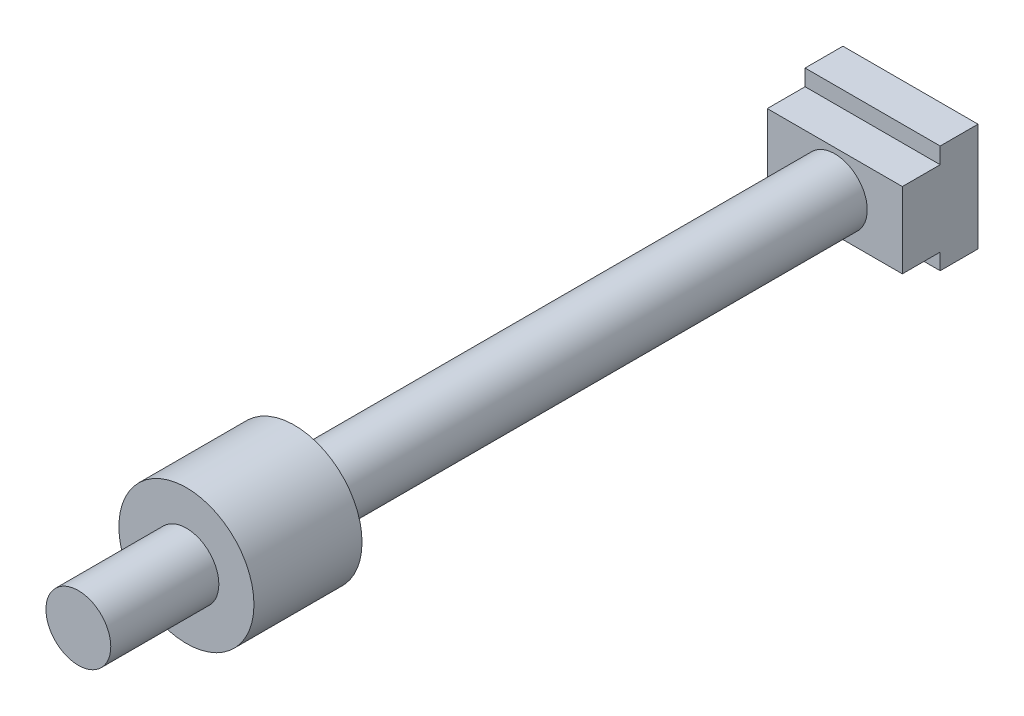
SolidWorks part; units mm, degrees
ref_plane "Front Plane" through (0, 0, 0) normal (0, 0, 1) x (1, 0, 0)
ref_plane "Top Plane" through (0, 0, 0) normal (0, 1, 0) x (1, 0, 0)
ref_plane "Right Plane" through (0, 0, 0) normal (1, 0, 0) x (0, 0, -1)
sketch "Sketch1" plane through (0, 0, 0) normal (0, 0, 1) x (1, 0, 0)
  circle A0 centre (0, 0) radius 6
  dimension "D1" = 12
extrude "Boss-Extrude1" add sketch "Sketch1" along normal blind 100
sketch "Sketch2" plane through (0, 0, 100) normal (0, 0, 1) x (1, 0, 0)
  circle A0 centre (0, 0) radius 12.5
  dimension "D1" = 25
extrude "Boss-Extrude2" add sketch "Sketch2" along normal blind 20
sketch "Sketch3" plane through (0, 0, 120) normal (0, 0, 1) x (1, 0, 0)
  circle A0 centre (0, 0) radius 6
  dimension "D1" = 12
extrude "Boss-Extrude3" add sketch "Sketch3" along normal blind 20
sketch "Sketch4" plane through (0, 0, 0) normal (0, 0, -1) x (-1, 0, 0)
  line L1 (-12.5, -7) -> (12.5, -7)
  line L2 (-12.5, -7) -> (-12.5, 7)
  line L3 (-12.5, 7) -> (12.5, 7)
  line L4 (12.5, -7) -> (12.5, 7)
  line L5 (-12.5, -7) -> (12.5, 7) construction
  line L6 (-12.5, 7) -> (12.5, -7) construction
  point P0 (0, 0)
  dimension "D1" = 14
  dimension "D2" = 25
extrude "Boss-Extrude4" add sketch "Sketch4" along normal blind 7
sketch "Sketch5" plane through (0, 0, -7) normal (0, 0, -1) x (-1, 0, 0)
  line L0 (-12.5, 7) -> (-12.5, -7) construction
  line L1 (-12.5, -10) -> (12.5, -10)
  line L2 (-12.5, -10) -> (-12.5, 10)
  line L3 (-12.5, 10) -> (12.5, 10)
  line L4 (12.5, -10) -> (12.5, 10)
  line L5 (-12.5, -10) -> (12.5, 10) construction
  line L6 (-12.5, 10) -> (12.5, -10) construction
  point P0 (0, 0)
  dimension "D1" = 20
extrude "Boss-Extrude5" add sketch "Sketch5" along normal blind 7
